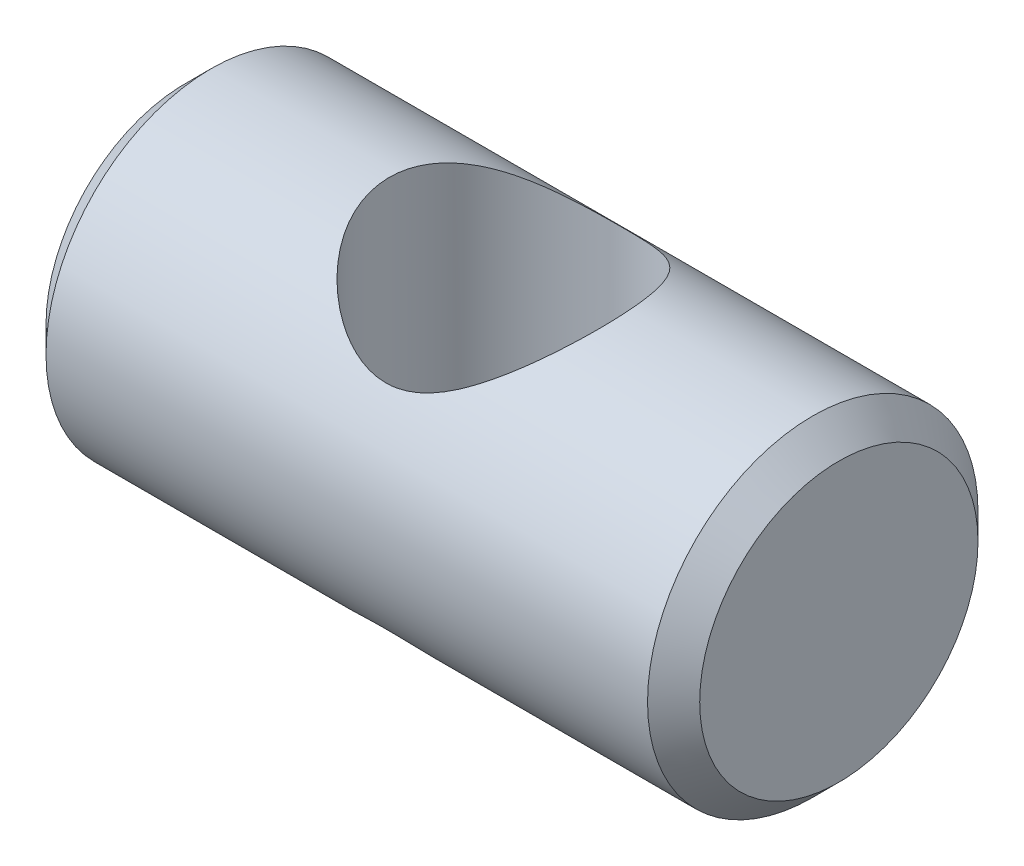
SolidWorks part; units mm, degrees
ref_plane "Front Plane" through (0, 0, 0) normal (0, 0, 1) x (1, 0, 0)
ref_plane "Top Plane" through (0, 0, 0) normal (0, 1, 0) x (1, 0, 0)
ref_plane "Right Plane" through (0, 0, 0) normal (1, 0, 0) x (0, 0, -1)
sketch "Sketch1" plane through (0, 0, 0) normal (1, 0, 0) x (0, 0, -1)
  circle A0 centre (0, 0) radius 4.815
  dimension "D1" = 9.63
extrude "Boss-Extrude1" add sketch "Sketch1" along normal mid plane 19.05
chamfer "Chamfer1" distance 0.76 angle 45 2 edges at (9.525, 0, -4.815) (-9.525, 0, -4.815)
sketch "Sketch2" plane through (0, 0, 0) normal (0, 1, 0) x (1, 0, 0)
  circle A0 centre (0, -0.25) radius 3.43
  dimension "D1" = 6.86
  dimension "D2" = 0.25
extrude "Cut-Extrude1" cut sketch "Sketch2" against normal mid plane 190.5
